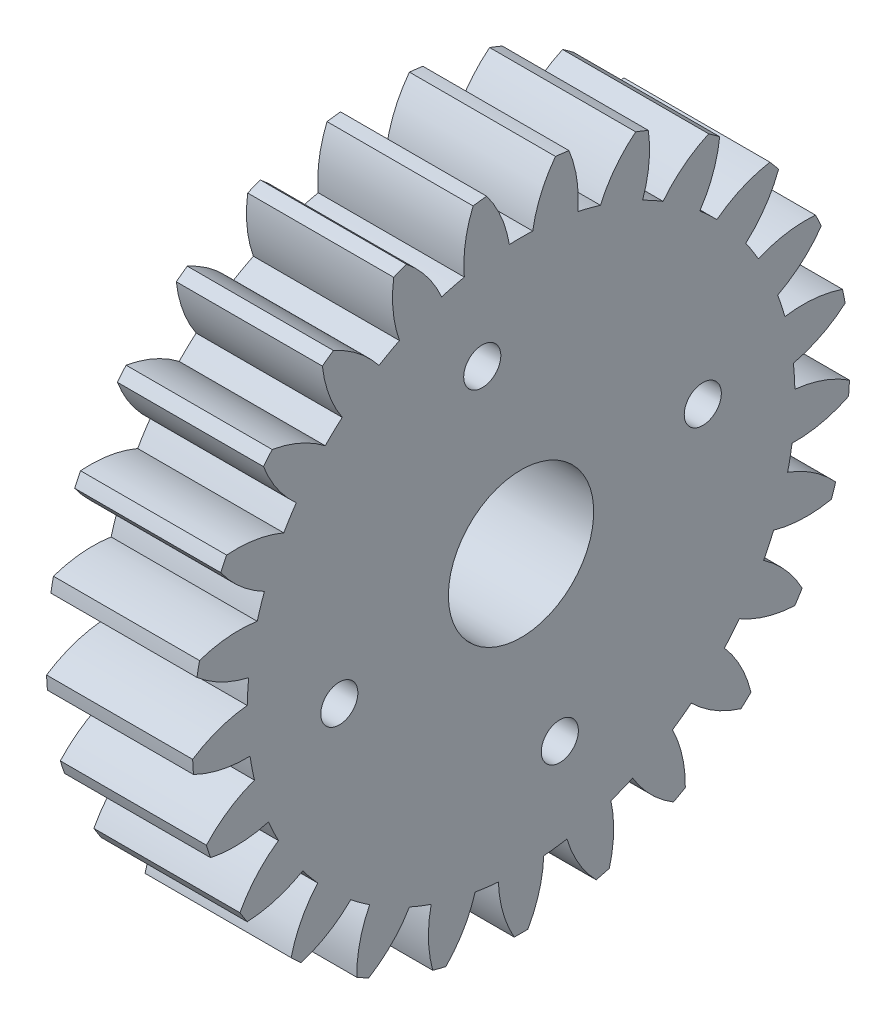
SolidWorks part; units mm, degrees
ref_plane "Plane1" through (0, 0, 0) normal (0, 0, 1) x (1, 0, 0)
ref_plane "Plane2" through (0, 0, 0) normal (0, 1, 0) x (1, 0, 0)
ref_plane "Plane3" through (0, 0, 0) normal (1, 0, 0) x (0, 0, -1)
sketch "HoldingSke" plane through (0, 0, 0) normal (0, 1, 0) x (1, 0, 0)
  line L0 (0, 0) -> (0.9063, -0.4226)
  line L1 (-15, 0) -> (100, 0) construction
  line L2 (0, 0) -> (-2.1039, 2.3779)
  line L3 (0, 0) -> (-11.863, 4.5341)
  line L4 (0, 0) -> (7.8269, 3.6497)
  line L5 (0, 0) -> (-46.8476, -17.4728)
  line L6 (0, 0) -> (-4.9738, -3.3558)
  line L7 (-2.1039, 2.3779) -> (8.6586, 51.2059)
  line L8 (-76.2, 54.61) -> (-75.3, 54.61)
  line L9 (-71.009, 38.7566) -> (-53.1078, 45.2721)
  line L10 (-76.2, 71.12) -> (104.1128, 71.12)
  line L11 (0, 0) -> (-6, 0)
  line L12 (-76.2, 101.6) -> (-76.162, 101.6)
  line L13 (24.9733, 27.94) -> (52.9518, 28.4284)
  line L14 (24.9733, 27.94) -> (24.9743, 27.94)
  line L15 (24.9733, 27.94) -> (100.4006, 29.5858)
  line L16 (-63.627, -1) -> (-12.827, -1)
  circle A0 centre (0, 0) radius 2.5
  circle A1 centre (0, 0) radius 11.249
  circle A2 centre (0, 0) radius 37.5
  circle A3 centre (0, 0) radius 2.5
  dimension "MHD" = 22.498
  dimension "Hub_dia" = 75
  dimension "Bore" = 5
  dimension "MBD" = 5
  dimension "Num_teeth" = 25
  dimension "Pitch_radius" = 180.3128
  dimension "Pitch" = 1
  dimension "Width" = 6
  dimension "Overall_len" = 50
  dimension "Show_teeth" = 25
  dimension "Thickness" = 6
  dimension "OAL" = 50.0001
  dimension "T_dim" = 0.9
  dimension "Ap" = 20
  dimension "H" = 19.05
  dimension "Backlash" = 0.038
  dimension "Addendum_fac" = 1
  dimension "Dedendum_fac" = 1.25
  dimension "Clearance_fac" = 0.25
  dimension "Dedendum_add" = 0.001
  dimension "Module" = 1
sketch "BasProSke" plane through (0, 0, 0) normal (0, 1, 0) x (1, 0, 0)
  line L0 (-10, 0) -> (60, 0) construction
  line L1 (0, 0) -> (0, 13.5)
  line L2 (0, 0) -> (6, 0)
  line L3 (6, 0) -> (6, 13.5)
  line L4 (6, 13.5) -> (0, 13.5)
  dimension "Diameter" = 27
  dimension "Thickness" = 6
revolve "Base-Revolve" add sketch "BasProSke" angle 360 about L0
sketch "TooCutSke" plane through (0, 0, 0) normal (1, 0, 0) x (0, 0, -1)
  line L1 (0, 0) -> (0, 107) construction
  line L2 (0, 0) -> (-0.8514, 12.471) construction
  line L3 (0, 0) -> (-3.1282, 24.7619) construction
  line L4 (-0.8514, 12.471) -> (-1.5641, 12.3809) construction
  arc A0 (0.4801, 11.2388) -> (-0.4801, 11.2388) centre (0, 0) ccw
  arc A1 (1.4322, 13.4494) -> (-1.4322, 13.4494) centre (0, 0) ccw
  circle A2 centre (0, 0) radius 12.5 construction
  circle A3 centre (0, 0) radius 11.7462 construction
  arc A4 (-0.4801, 11.2388) -> (-1.4322, 13.4494) centre (-5.4133, 10.4244) ccw
  arc A5 (1.4322, 13.4494) -> (0.4801, 11.2388) centre (5.4133, 10.4244) ccw
  dimension "Root_dia" = 22.498
  dimension "Overcut_dia" = 27.0508
  dimension "Pitch_dia" = 25
  dimension "Base_dia" = 23.4923
  dimension "Flank_rad" = 5
  dimension "Half_ang" = 7.2
  dimension "Half_CT" = 0.7184
extrude "ToothCut" cut sketch "TooCutSke" along normal through all
fillet "Breaks" [suppressed] radius 0.02
fillet "RootFillets" [suppressed] radius 0.251
pattern_circular "TeethCuts" count 25 every 14.4 about axis through (-10, 0, 0) along (1, 0, 0) of "ToothCut", "RootFillets", "Breaks"
sketch "HubNeaOneSke" plane through (0, 0, 0) normal (-1, 0, 0) x (0, 0, 1)
  circle A0 centre (0, 0) radius 11.249
  dimension "Diameter" = 22.498
extrude "HubNearOne" [suppressed] add sketch "HubNeaOneSke" along normal blind 44.0001
sketch "HubNeaBotSke" plane through (0, 0, 0) normal (-1, 0, 0) x (0, 0, 1)
  circle A0 centre (0, 0) radius 11.249
  dimension "Diameter" = 22.498
extrude "HubNearBoth" [suppressed] add sketch "HubNeaBotSke" along normal blind 22
ref_plane "FarPln" through (6, 0, 0) normal (1, 0, 0) x (0, 0, -1)
sketch "HubFarSke" plane through (6, 0, 0) normal (1, 0, 0) x (0, 0, -1)
  circle A0 centre (0, 0) radius 11.249
  dimension "Diameter" = 22.498
extrude "HubFar" [suppressed] add sketch "HubFarSke" along normal blind 22
sketch "BorSke" plane through (0, 0, 0) normal (1, 0, 0) x (0, 0, -1)
  circle A0 centre (0, 0) radius 2.5
  dimension "Diameter" = 5
extrude "Bore" cut sketch "BorSke" along normal mid plane 100.0001
sketch "KeySke" plane through (0, 0, 0) normal (1, 0, 0) x (0, 0, -1)
  line L0 (-1, 0) -> (-1, 3.4)
  line L1 (-1, 3.4) -> (1, 3.4)
  line L2 (1, 3.4) -> (1, 0)
  line L3 (0, 0) -> (0, 34) construction
  line L4 (-1, 0) -> (1, 0)
  dimension "Offset" = 3.4
  dimension "Width" = 2
extrude "Keyway" [suppressed] cut sketch "KeySke" along normal mid plane 100.0001
pattern_circular "Keyway2" [suppressed] count 2 every 90 about axis through (-10, 0, 0) along (1, 0, 0)
extrude "Cut-Extrude1" cut sketch "Sketch1" against normal through all
sketch "Sketch1" plane through (0, -120.077, 51.3832) normal (-1, 0, 0) x (0, 0.1818, 0.9833)
  circle A116 centre (-21.6513, 124.4927) radius 0.762
  circle A119 centre (-25.7781, 134.4669) radius 0.762
  circle A122 centre (-35.7524, 130.3401) radius 0.762
  circle A125 centre (-31.6255, 120.3658) radius 0.762
  circle A128 centre (-28.7018, 127.4164) radius 2.9845
equation "' \"Module@HoldingSke\" = 6.35"
equation "' \"Num_teeth@HoldingSke\" = 12"
equation "' \"Ap@HoldingSke\" =  20"
equation "' \"Width@HoldingSke\" = 0.5 * 25.4"
equation "' \"Hub_dia@HoldingSke\"= 1 * 25.4"
equation "' \"Overall_len@HoldingSke\" = 1.0 * 25.4"
equation "' \"Bore@HoldingSke\" = 0.75 * 25.4"
equation "' \"T_dim@HoldingSke\" = 0.1 * 25.4"
equation "' \"Width@KeySke\" = 0.25 * 25.4"
equation "' \"Show_teeth@HoldingSke\" = 13"
equation "' \"Backlash@HoldingSke\" = 0.009 * 25.4"
equation "' \"Addendum_fac@HoldingSke\" = 1.0"
equation "' \"Dedendum_fac@HoldingSke\" = 1.25"
equation "' \"Dedendum_add@HoldingSke\" = 0.00005 * 25.4"
equation "' \"Clearance_fac@HoldingSke\" = 0.25"
equation "\"Pitch@HoldingSke\" = 1 / \"Module@HoldingSke\""
equation "\"Overcut_dia@TooCutSke\" = (\"Num_teeth@HoldingSke\" + 2 * \"Addendum_fac@HoldingSke\") / \"Pitch@HoldingSke\" + 0.002 * 25.4"
equation "\"Pitch_dia@TooCutSke\" = \"Num_teeth@HoldingSke\" / \"Pitch@HoldingSke\""
equation "\"Base_dia@TooCutSke\" = \"Num_teeth@HoldingSke\" / \"Pitch@HoldingSke\" * cos((\"Ap@HoldingSke\"  * 3.14159265 / 180))"
equation "\"Root_dia@TooCutSke\" = (\"Num_teeth@HoldingSke\" + 2) / \"Pitch@HoldingSke\" - 2 * (\"Addendum_fac@HoldingSke\" + \"Dedendum_fac@HoldingSke\") / \"Pitch@HoldingSke\" - \"Dedendum_add@HoldingSke\" * 2"
equation "\"Half_ang@TooCutSke\" = 180 / \"Num_teeth@HoldingSke\""
equation "\"Half_CT@TooCutSke\" = \"Num_teeth@HoldingSke\" / \"Pitch@HoldingSke\" * sin((3.14159265 / 2 / \"Num_teeth@HoldingSke\")) / 2 - 7 * \"Backlash@HoldingSke\" / 4"
equation "\"Flank_rad@TooCutSke\" = \"Num_teeth@HoldingSke\" / \"Pitch@HoldingSke\" / 5"
equation "\"Radius@RootFillets\" = \"Clearance_fac@HoldingSke\" / \"Pitch@HoldingSke\" + \"Dedendum_add@HoldingSke\""
equation "\"Break_rad@Breaks\" = 0.02 / \"Pitch@HoldingSke\""
equation "\"Thickness@HoldingSke\" = \"Width@HoldingSke\""
equation "\"OAL@HoldingSke\" = \"Thickness@HoldingSke\""
equation "\"MHD@HoldingSke\" = (\"Num_teeth@HoldingSke\" + 2) / \"Pitch@HoldingSke\" - 2 * (\"Addendum_fac@HoldingSke\" + \"Dedendum_fac@HoldingSke\")  / \"Pitch@HoldingSke\" - \"Dedendum_add@HoldingSke\" * 2"
equation "\"MBD@HoldingSke\" = (\"Num_teeth@HoldingSke\" + 2) / \"Pitch@HoldingSke\" - 2 * (\"Addendum_fac@HoldingSke\" + \"Dedendum_fac@HoldingSke\")  / \"Pitch@HoldingSke\" - \"Dedendum_add@HoldingSke\" * 2 - 0.002 * 25.4"
equation "\"MHD@HoldingSke\" = ((sgn( \"MHD@HoldingSke\" - \"Hub_dia@HoldingSke\" )-1)*( \"MHD@HoldingSke\" - \"Hub_dia@HoldingSke\" ))/-2+ \"Hub_dia@HoldingSke\""
equation "\"MBD@HoldingSke\" = ((sgn( \"MBD@HoldingSke\" - \"Bore@HoldingSke\" )-1)*( \"MBD@HoldingSke\" - \"Bore@HoldingSke\" ))/-2+ \"Bore@HoldingSke\""
equation "\"OAL@HoldingSke\" = ((sgn( \"OAL@HoldingSke\" - \"Overall_len@HoldingSke\" )+1)*( \"OAL@HoldingSke\" - \"Overall_len@HoldingSke\" ))/2 + \"Overall_len@HoldingSke\" + 0.000002 * 25.4"
equation "\"Num_teeth@TeethCuts\" = int( \"Show_teeth@HoldingSke\" ) + 1"
equation "\"Num_teeth@TeethCuts\" = ((sgn( \"Num_teeth@TeethCuts\" - \"Num_teeth@HoldingSke\" )-1)*( \"Num_teeth@TeethCuts\" - \"Num_teeth@HoldingSke\" ))/-2+ \"Num_teeth@HoldingSke\""
equation "\"Num_teeth@TeethCuts\" = ((sgn( \"Num_teeth@TeethCuts\" - 2.0)+1)*( \"Num_teeth@TeethCuts\" - 2.0))/2 +2.0"
equation "\"Angle@TeethCuts\" = 360.0 / \"Num_teeth@HoldingSke\""
equation "\"Diameter@BasProSke\" = (\"Num_teeth@HoldingSke\" + 2 * \"Addendum_fac@HoldingSke\") / \"Pitch@HoldingSke\""
equation "\"Thickness@BasProSke\"  = \"Thickness@HoldingSke\""
equation "' \"Fillet_rad@BasProSke\" =  \"Thickness@HoldingSke\" * 0.05"
equation "\"MHD@HoldingSke\" = ((sgn( \"MHD@HoldingSke\" - \"Root_dia@TooCutSke\" )-1)*( \"MHD@HoldingSke\" - \"Root_dia@TooCutSke\" ))/-2+ \"Root_dia@TooCutSke\""
equation "\"Diameter@HubNeaOneSke\" = \"MHD@HoldingSke\""
equation "\"Length@HubNearOne\" = \"OAL@HoldingSke\" - \"Thickness@BasProSke\""
equation "\"Diameter@HubNeaBotSke\" = \"MHD@HoldingSke\""
equation "\"Length@HubNearBoth\" = ( \"OAL@HoldingSke\" - \"Thickness@BasProSke\" ) / 2.0"
equation "\"Thickness@FarPln\" = \"Thickness@BasProSke\""
equation "\"Diameter@HubFarSke\" = \"MHD@HoldingSke\""
equation "\"Length@HubFar\" = ( \"OAL@HoldingSke\" - \"Thickness@BasProSke\" ) / 2.0"
equation "\"Diameter@BorSke\" = \"MBD@HoldingSke\""
equation "\"D1@Bore\" = \"OAL@HoldingSke\" * 2.0"
equation "\"D1@Keyway\" = \"OAL@HoldingSke\" * 2.0"
equation "\"Offset@KeySke\" = \"T_dim@HoldingSke\" + \"MBD@HoldingSke\" / 2.0"
